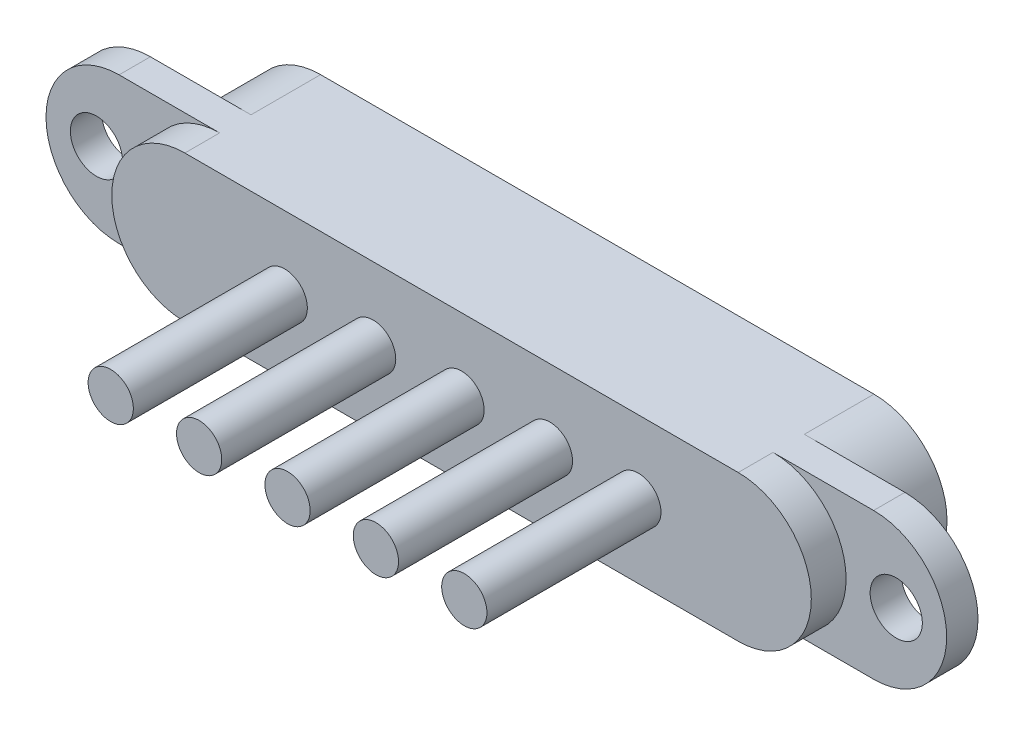
SolidWorks part; units mm, degrees
ref_plane "Front Plane" through (0, 0, 0) normal (0, 0, 1) x (1, 0, 0)
ref_plane "Top Plane" through (0, 0, 0) normal (0, 1, 0) x (1, 0, 0)
ref_plane "Right Plane" through (0, 0, 0) normal (1, 0, 0) x (0, 0, -1)
sketch "Sketch1" plane through (0, 0, 0) normal (0, 0, 1) x (1, 0, 0)
  line L0 (-7.95, 0) -> (7.95, 0) construction
  line L1 (-7.95, 2.1) -> (7.95, 2.1)
  line L2 (-7.95, -2.1) -> (7.95, -2.1)
  arc A0 (-7.95, 2.1) -> (-7.95, -2.1) centre (-7.95, 0) ccw
  arc A1 (7.95, -2.1) -> (7.95, 2.1) centre (7.95, 0) ccw
  point P2 (0, 0)
  dimension "D2" = 20.1
  dimension "D1" = 4.2
extrude "Boss-Extrude1" add sketch "Sketch1" along normal blind 2
sketch "Sketch2" plane through (0, 0, 2) normal (0, 0, 1) x (1, 0, 0)
  line L0 (-10.84, 0) -> (10.84, 0) construction
  line L1 (-10.84, 2.1) -> (10.84, 2.1)
  line L2 (-10.84, -2.1) -> (10.84, -2.1)
  line L3 (7.95, 2.1) -> (-7.95, 2.1) construction
  arc A0 (-10.84, 2.1) -> (-10.84, -2.1) centre (-10.84, 0) ccw
  arc A1 (10.84, -2.1) -> (10.84, 2.1) centre (10.84, 0) ccw
  point P2 (0, 0)
  dimension "D1" = 25.88
extrude "Boss-Extrude2" add sketch "Sketch2" along normal blind 0.9
sketch "Sketch3" plane through (0, 0, 2) normal (0, 0, -1) x (-1, 0, 0)
  line L0 (-12.94, 0) -> (12.94, 0) construction
  line L1 (-11.49, 0) -> (0, 2.1) construction
  line L2 (-7.95, 2.1) -> (7.95, 2.1) construction
  line L3 (0, 2.1) -> (11.49, 0) construction
  arc A0 (-10.84, 2.1) -> (-10.84, -2.1) centre (-10.84, 0) ccw construction
  arc A1 (10.84, -2.1) -> (10.84, 2.1) centre (10.84, 0) ccw construction
  circle A2 centre (-11.49, 0) radius 0.75
  circle A3 centre (11.49, 0) radius 0.75
  dimension "D1" = 22.98
  dimension "D2" = 1.5
extrude "Cut-Extrude1" cut sketch "Sketch3" against normal blind 0.9
sketch "Sketch4" plane through (0, 0, 0) normal (0, 0, -1) x (-1, 0, 0)
  line L0 (-10.05, 0) -> (10.05, 0) construction
  line L1 (-8, 0) -> (0, 2.1) construction
  line L2 (-7.95, 2.1) -> (7.95, 2.1) construction
  line L3 (0, 2.1) -> (8, 0) construction
  arc A0 (-7.95, 2.1) -> (-7.95, -2.1) centre (-7.95, 0) ccw construction
  arc A1 (7.95, -2.1) -> (7.95, 2.1) centre (7.95, 0) ccw construction
  circle A2 centre (0, 0) radius 0.65
  circle A3 centre (2.54, 0) radius 0.65
  circle A4 centre (5.08, 0) radius 0.65
  circle A5 centre (-2.54, 0) radius 0.65
  circle A6 centre (-5.08, 0) radius 0.65
  circle A7 centre (-8, 0) radius 1.5
  circle A8 centre (8, 0) radius 1.5
  dimension "D1" = 1.3
  dimension "D6" = 16
  dimension "D7" = 3
  dimension "D4" = 2.54
  dimension "D5" = 2.54
  dimension "D2" = 3
  dimension "D3" = 3
extrude "Cut-Extrude2" cut sketch "Sketch4" against normal blind 0.1
sketch "Sketch5" plane through (0, 0, 2.9) normal (0, 0, 1) x (1, 0, 0)
  line L2 (7.95, 2.1) -> (-7.95, 2.1)
  line L3 (-7.95, -2.1) -> (7.95, -2.1)
  line L4 (7.95, 2.1) -> (-7.95, 2.1)
  line L5 (-7.95, -2.1) -> (7.95, -2.1)
  arc A2 (-7.95, 2.1) -> (-7.95, -2.1) centre (-7.95, 0) ccw
  arc A3 (7.95, -2.1) -> (7.95, 2.1) centre (7.95, 0) ccw
  arc A4 (-7.95, 2.1) -> (-7.95, -2.1) centre (-7.95, 0) ccw
  arc A5 (7.95, -2.1) -> (7.95, 2.1) centre (7.95, 0) ccw
  dimension "D1" = 0
extrude "Boss-Extrude3" add sketch "Sketch5" along normal blind 1
sketch "Sketch6" plane through (0, 0, 3.9) normal (0, 0, 1) x (1, 0, 0)
  circle A1 centre (-5.08, 0) radius 0.65
  circle A2 centre (-5.08, 0) radius 0.65
  circle A3 centre (-2.54, 0) radius 0.65
  circle A4 centre (-2.54, 0) radius 0.65
  circle A5 centre (0, 0) radius 0.65
  circle A6 centre (0, 0) radius 0.65
  circle A7 centre (2.54, 0) radius 0.65
  circle A8 centre (2.54, 0) radius 0.65
  circle A9 centre (5.08, 0) radius 0.65
  circle A10 centre (5.08, 0) radius 0.65
  dimension "D1" = 0
  dimension "D2" = 0
  dimension "D3" = 0
  dimension "D4" = 0
  dimension "D5" = 0
extrude "Boss-Extrude4" add sketch "Sketch6" along normal blind 5
